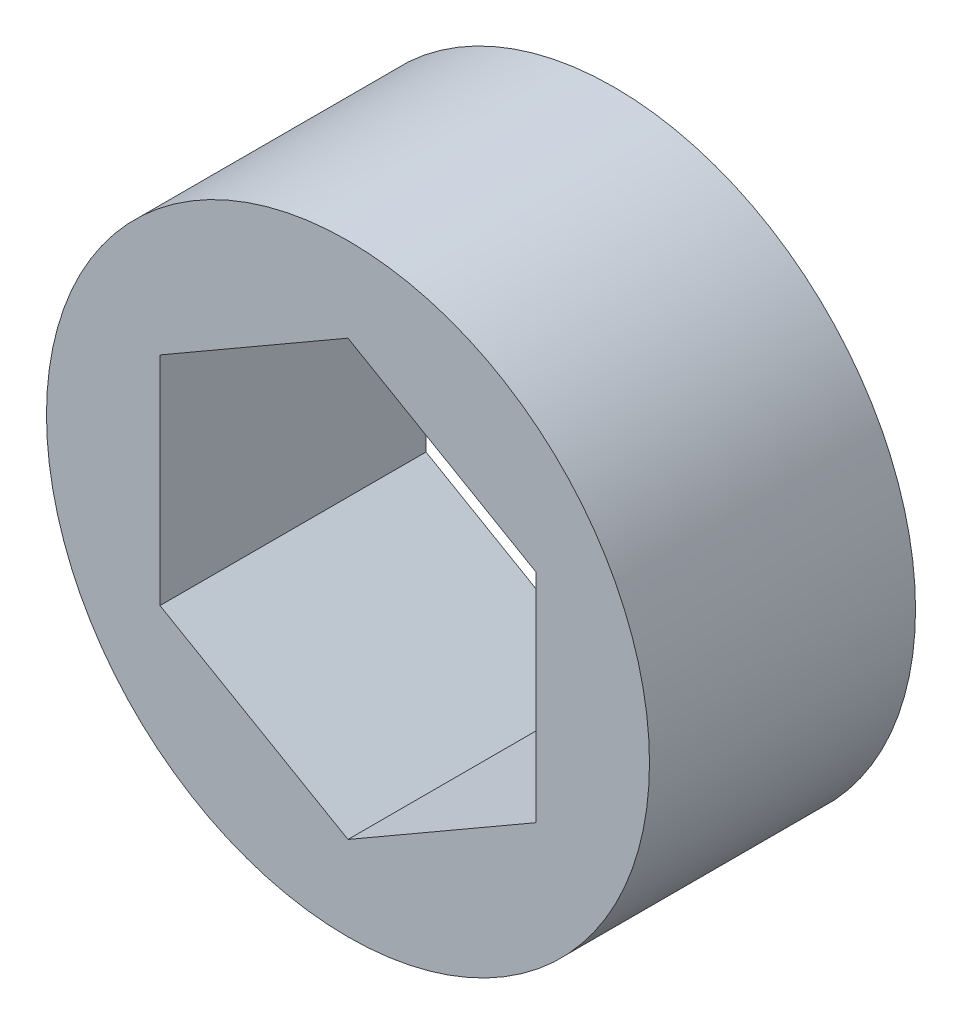
SolidWorks part; units mm, degrees
material "Nylon 101"
ref_plane "Front Plane" through (0, 0, 0) normal (0, 0, 1) x (1, 0, 0)
ref_plane "Top Plane" through (0, 0, 0) normal (0, 1, 0) x (1, 0, 0)
ref_plane "Right Plane" through (0, 0, 0) normal (1, 0, 0) x (0, 0, -1)
sketch "Sketch1" plane through (0, 0, 0) normal (0, 0, 1) x (1, 0, 0)
  line L1 (6.731, 3.8861) -> (0, 7.7723)
  line L2 (0, 7.7723) -> (-6.731, 3.8861)
  line L3 (-6.731, 3.8861) -> (-6.731, -3.8861)
  line L4 (-6.731, -3.8861) -> (0, -7.7723)
  line L5 (0, -7.7723) -> (6.731, -3.8861)
  line L6 (6.731, -3.8861) -> (6.731, 3.8861)
  circle A0 centre (0, 0) radius 6.731 construction
  circle A1 centre (0, 0) radius 10.795
  dimension "D1" = 13.462
  dimension "D2" = 21.59
extrude "Boss-Extrude1" add sketch "Sketch1" along normal blind 9.525
